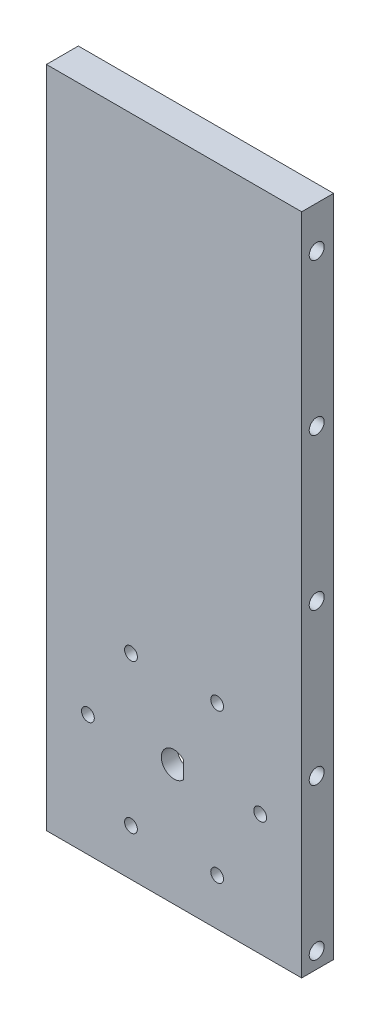
SolidWorks part; units mm, degrees
material "PLA"
ref_plane "Alzado" through (0, 0, 0) normal (0, 0, 1) x (1, 0, 0)
ref_plane "Planta" through (0, 0, 0) normal (0, 1, 0) x (1, 0, 0)
ref_plane "Vista lateral" through (0, 0, 0) normal (1, 0, 0) x (0, 0, -1)
sketch "Croquis1" plane through (0, 0, 0) normal (0, 0, 1) x (1, 0, 0)
  line L1 (0, 0) -> (80, 0)
  line L2 (0, 0) -> (0, 200)
  line L3 (0, 200) -> (80, 200)
  line L4 (80, 0) -> (80, 200)
  dimension "D1" = 200
  dimension "D2" = 80
extrude "Saliente-Extruir1" add sketch "Croquis1" along normal blind 10
sketch "Croquis2" plane through (0, 0, 10) normal (0, 0, 1) x (1, 0, 0)
  line L0 (0, 0) -> (80, 0) construction
  line L1 (0, 200) -> (0, 0) construction
  line L2 (42.9047, 27.25) -> (42.9047, 32.75)
  arc A0 (42.9047, 32.75) -> (42.9047, 27.25) centre (40, 30) ccw
  dimension "D2" = 8
  dimension "D1" = 30
  dimension "D3" = 40
  dimension "D4" = 5.5
extrude "Cortar-Extruir1" cut sketch "Croquis2" against normal blind 10
sketch "Croquis5" plane through (0, 0, 0) normal (0, 0, -1) x (-1, 0, 0)
  line L0 (-40, 30) -> (-40, 65) construction
  line L1 (-40, 30) -> (-5, 30) construction
  circle A0 centre (-40, 30) radius 35 construction
  circle A1 centre (-13, 30) radius 2
  circle A2 centre (-26.5, 6.6173) radius 2
  circle A3 centre (-53.5, 6.6173) radius 2
  circle A4 centre (-67, 30) radius 2
  circle A5 centre (-53.5, 53.3827) radius 2
  circle A6 centre (-26.5, 53.3827) radius 2
  dimension "D1" = 70
  dimension "D2" = 4
  dimension "D3" = 8
  dimension "D4" = 6
extrude "Cortar-Extruir4" cut sketch "Croquis5" against normal through all
sketch "Croquis6" plane through (0, 0, 0) normal (0, 0, -1) x (-1, 0, 0)
  circle A0 centre (-40, 30) radius 35
  dimension "D1" = 70
extrude "Cortar-Extruir5" cut sketch "Croquis6" against normal blind 5
sketch "Croquis7" plane through (0, 0, 10) normal (0, 0, 1) x (1, 0, 0)
  line L0 (0, 0) -> (0, -8)
  line L1 (0, -8) -> (80, -8)
  line L2 (80, -8) -> (80, 0)
  line L4 (0, 0) -> (80, 0) construction
  line L5 (0, 0) -> (80, 0)
  dimension "D1" = 8
extrude "Saliente-Extruir2" add sketch "Croquis7" against normal blind 10
sketch "Croquis9" plane through (0, 0, 0) normal (0, 0, -1) x (-1, 0, 0)
  circle A0 centre (-40, 30) radius 35
extrude "Cortar-Extruir7" cut sketch "Croquis9" against normal blind 5
sketch "Croquis11" plane through (0, 0, 0) normal (-1, 0, 0) x (0, 0, 1)
  line L1 (10, 200) -> (0, 200) construction
  line L2 (5, 200) -> (5, -8) construction
  line L3 (0, -8) -> (10, -8) construction
  circle A0 centre (5, 187) radius 2.35
  circle A1 centre (5, 139.5) radius 2.35
  circle A2 centre (5, 92) radius 2.35
  circle A3 centre (5, 44.5) radius 2.35
  circle A4 centre (5, -3) radius 2.35
  point P8 (0, 0)
  dimension "D2" = 4.7
  dimension "D1" = 13
  dimension "D3" = 5
extrude "Cortar-Extruir8" cut sketch "Croquis11" against normal blind 5
sketch "Croquis12" plane through (80, 0, 0) normal (1, 0, 0) x (0, 0, -1)
  line L0 (-10, 200) -> (0, 200) construction
  line L1 (-5, 200) -> (-5, -8) construction
  line L2 (0, -8) -> (-10, -8) construction
  circle A0 centre (-5.2858, 187) radius 2.35
  circle A1 centre (-5.2858, 139.5) radius 2.35
  circle A2 centre (-5.2858, 92) radius 2.35
  circle A3 centre (-5.2858, 44.5) radius 2.35
  circle A4 centre (-5.2858, -3) radius 2.35
  dimension "D2" = 4.7
  dimension "D1" = 13
  dimension "D3" = 5
extrude "Cortar-Extruir9" cut sketch "Croquis12" against normal blind 5
